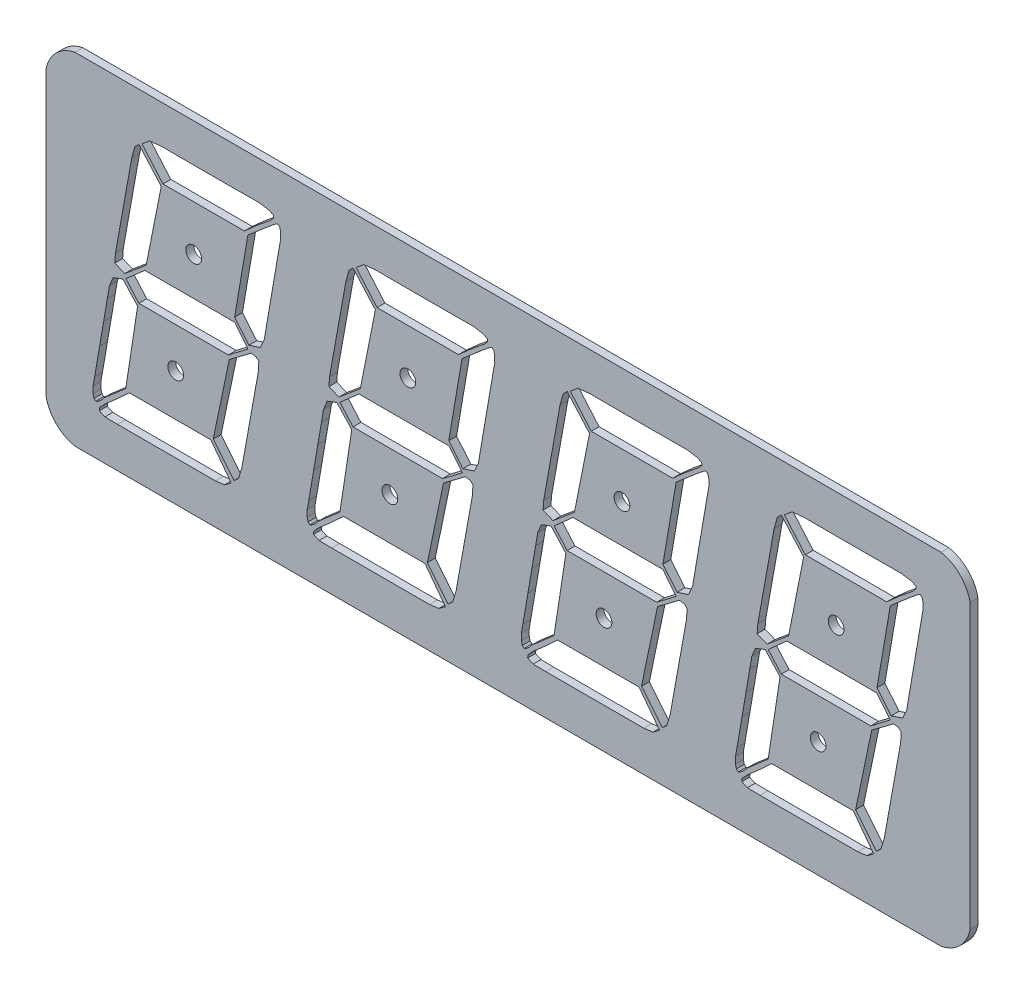
SolidWorks part; units mm, degrees
material "Maple"
ref_plane "Alzado" through (0, 0, 0) normal (0, 0, 1) x (1, 0, 0)
ref_plane "Planta" through (0, 0, 0) normal (0, 1, 0) x (1, 0, 0)
ref_plane "Vista lateral" through (0, 0, 0) normal (1, 0, 0) x (0, 0, -1)
sketch "Model" plane through (0, 0, 0) normal (0, 0, 1) x (1, 0, 0)
  line L311 (169.8255, 67.5031) -> (-160.1745, 67.5031)
  line L328 (148.1981, -37.5509) -> (154.411, -3.0611)
  line L329 (154.411, -3.0611) -> (154.6215, 0.6431)
  line L330 (154.6215, 0.6431) -> (153.5658, 1.5691)
  line L331 (153.5658, 1.5691) -> (151.7361, 1.8778)
  line L332 (151.7361, 1.8778) -> (143.3814, -4.3918)
  line L333 (143.3814, -4.3918) -> (137.2644, -33.698)
  line L334 (137.2644, -33.698) -> (145.1642, -43.466)
  line L335 (145.1642, -43.466) -> (146.9003, -41.9023)
  line L336 (146.9003, -41.9023) -> (148.1981, -37.5509)
  line L337 (106.2034, 43.4858) -> (99.9905, 8.9954)
  line L338 (99.9905, 8.9954) -> (99.7437, 5.6062)
  line L339 (99.7437, 5.6062) -> (103.5436, 4.0578)
  line L340 (103.5436, 4.0578) -> (111.7133, 10.9097)
  line L341 (111.7133, 10.9097) -> (117.4489, 39.7707)
  line L342 (117.4489, 39.7707) -> (108.9383, 49.3712)
  line L343 (108.9383, 49.3712) -> (107.4078, 47.8277)
  line L344 (107.4078, 47.8277) -> (106.2034, 43.4858)
  line L345 (150.4696, 40.2183) -> (145.4043, 10.6009)
  line L346 (145.4043, 10.6009) -> (150.8256, 4.0578)
  line L347 (150.8256, 4.0578) -> (155.1565, 5.4502)
  line L348 (155.1565, 5.4502) -> (156.7122, 8.8717)
  line L349 (156.7122, 8.8717) -> (157.4944, 13.4819)
  line L350 (157.4944, 13.4819) -> (158.8939, 21.6593)
  line L351 (158.8939, 21.6593) -> (160.4266, 30.5868)
  line L352 (160.4266, 30.5868) -> (162.3405, 41.7165)
  line L353 (162.3405, 41.7165) -> (162.9375, 45.066)
  line L354 (162.9375, 45.066) -> (162.9221, 47.52)
  line L355 (162.9221, 47.52) -> (162.5691, 48.9124)
  line L356 (162.5691, 48.9124) -> (161.868, 49.5374)
  line L357 (161.868, 49.5374) -> (161.7578, 49.5282)
  line L358 (161.7578, 49.5282) -> (161.635, 49.4837)
  line L359 (161.635, 49.4837) -> (161.3364, 49.3229)
  line L360 (161.3364, 49.3229) -> (160.5503, 48.7761)
  line L361 (160.5503, 48.7761) -> (158.3402, 46.9717)
  line L362 (158.3402, 46.9717) -> (150.4696, 40.2183)
  line L363 (96.1085, -42.7715) -> (94.0111, -44.9746)
  line L364 (94.0111, -44.9746) -> (93.8733, -46.1445)
  line L365 (93.8733, -46.1445) -> (95.9736, -47.1243)
  line L366 (95.9736, -47.1243) -> (100.8421, -47.1738)
  line L367 (100.8421, -47.1738) -> (138.1093, -47.1738)
  line L368 (138.1093, -47.1738) -> (141.5938, -46.7307)
  line L369 (141.5938, -46.7307) -> (144.1378, -44.8847)
  line L370 (144.1378, -44.8847) -> (136.3412, -34.5114)
  line L371 (136.3412, -34.5114) -> (105.3033, -34.5114)
  line L372 (105.3033, -34.5114) -> (100.112, -39.2778)
  line L373 (100.112, -39.2778) -> (96.1085, -42.7715)
  line L374 (143.0175, -3.1636) -> (150.4696, 2.5031)
  line L375 (150.4696, 2.5031) -> (145.3202, 8.8399)
  line L376 (145.3202, 8.8399) -> (111.039, 8.8399)
  line L377 (111.039, 8.8399) -> (103.9773, 2.5031)
  line L378 (103.9773, 2.5031) -> (108.9226, -3.1636)
  line L379 (108.9226, -3.1636) -> (143.0175, -3.1636)
  line L380 (159.0632, 49.2759) -> (160.2858, 50.6364)
  line L381 (160.2858, 50.6364) -> (160.1964, 51.4631)
  line L382 (160.1964, 51.4631) -> (158.7577, 52.3004)
  line L383 (158.7577, 52.3004) -> (154.753, 52.948)
  line L384 (154.753, 52.948) -> (142.5301, 52.905)
  line L385 (142.5301, 52.905) -> (132.6069, 52.8858)
  line L386 (132.6069, 52.8858) -> (123.3038, 52.8961)
  line L387 (123.3038, 52.8961) -> (117.726, 52.945)
  line L388 (117.726, 52.945) -> (112.9865, 52.4395)
  line L389 (112.9865, 52.4395) -> (110.1277, 50.0329)
  line L390 (110.1277, 50.0329) -> (118.0876, 40.8073)
  line L391 (118.0876, 40.8073) -> (149.1255, 40.8073)
  line L392 (149.1255, 40.8073) -> (153.9859, 45.1352)
  line L393 (153.9859, 45.1352) -> (159.0632, 49.2759)
  line L394 (66.6066, -37.5826) -> (72.8195, -3.0928)
  line L395 (72.8195, -3.0928) -> (73.03, 0.6113)
  line L396 (73.03, 0.6113) -> (71.9743, 1.5374)
  line L397 (71.9743, 1.5374) -> (70.1446, 1.8461)
  line L398 (70.1446, 1.8461) -> (61.7899, -4.4236)
  line L399 (61.7899, -4.4236) -> (55.6728, -33.7298)
  line L400 (55.6728, -33.7298) -> (63.5727, -43.4977)
  line L401 (63.5727, -43.4977) -> (65.3088, -41.9341)
  line L402 (65.3088, -41.9341) -> (66.6066, -37.5826)
  line L403 (24.6119, 43.4541) -> (18.399, 8.9636)
  line L404 (18.399, 8.9636) -> (18.1522, 5.5745)
  line L405 (18.1522, 5.5745) -> (21.9521, 4.026)
  line L406 (21.9521, 4.026) -> (30.1218, 10.8779)
  line L407 (30.1218, 10.8779) -> (35.8574, 39.7389)
  line L408 (35.8574, 39.7389) -> (27.3468, 49.3394)
  line L409 (27.3468, 49.3394) -> (25.8163, 47.7959)
  line L410 (25.8163, 47.7959) -> (24.6119, 43.4541)
  line L411 (68.8781, 40.1866) -> (63.8128, 10.5692)
  line L412 (63.8128, 10.5692) -> (69.2341, 4.026)
  line L413 (69.2341, 4.026) -> (73.565, 5.4185)
  line L414 (73.565, 5.4185) -> (75.1207, 8.8399)
  line L415 (75.1207, 8.8399) -> (75.9029, 13.4502)
  line L416 (75.9029, 13.4502) -> (77.3024, 21.6276)
  line L417 (77.3024, 21.6276) -> (78.8351, 30.5551)
  line L418 (78.8351, 30.5551) -> (80.7489, 41.6847)
  line L419 (80.7489, 41.6847) -> (81.346, 45.0342)
  line L420 (81.346, 45.0342) -> (81.3306, 47.4882)
  line L421 (81.3306, 47.4882) -> (80.9776, 48.8806)
  line L422 (80.9776, 48.8806) -> (80.2764, 49.5056)
  line L423 (80.2764, 49.5056) -> (80.1663, 49.4964)
  line L424 (80.1663, 49.4964) -> (80.0435, 49.452)
  line L425 (80.0435, 49.452) -> (79.7449, 49.2912)
  line L426 (79.7449, 49.2912) -> (78.9588, 48.7444)
  line L427 (78.9588, 48.7444) -> (76.7487, 46.9399)
  line L428 (76.7487, 46.9399) -> (68.8781, 40.1866)
  line L429 (14.517, -42.7715) -> (12.4196, -44.9746)
  line L430 (12.4196, -44.9746) -> (12.2818, -46.1445)
  line L431 (12.2818, -46.1445) -> (14.3821, -47.1243)
  line L432 (14.3821, -47.1243) -> (19.2505, -47.1738)
  line L433 (19.2505, -47.1738) -> (56.5178, -47.1738)
  line L434 (56.5178, -47.1738) -> (60.0023, -46.7307)
  line L435 (60.0023, -46.7307) -> (62.5462, -44.8847)
  line L436 (62.5462, -44.8847) -> (54.7497, -34.5114)
  line L437 (54.7497, -34.5114) -> (23.7118, -34.5114)
  line L438 (23.7118, -34.5114) -> (18.5205, -39.2778)
  line L439 (18.5205, -39.2778) -> (14.517, -42.7715)
  line L440 (61.426, -3.1636) -> (68.8781, 2.5031)
  line L441 (68.8781, 2.5031) -> (63.8128, 8.8399)
  line L442 (63.8128, 8.8399) -> (29.5316, 8.8399)
  line L443 (29.5316, 8.8399) -> (22.3858, 2.5031)
  line L444 (22.3858, 2.5031) -> (27.3311, -3.1636)
  line L445 (27.3311, -3.1636) -> (61.426, -3.1636)
  line L446 (77.4717, 49.2759) -> (78.6943, 50.6364)
  line L447 (78.6943, 50.6364) -> (78.6049, 51.4631)
  line L448 (78.6049, 51.4631) -> (77.1662, 52.3004)
  line L449 (77.1662, 52.3004) -> (73.1615, 52.948)
  line L450 (73.1615, 52.948) -> (60.9385, 52.905)
  line L451 (60.9385, 52.905) -> (51.0154, 52.8858)
  line L452 (51.0154, 52.8858) -> (41.7123, 52.8961)
  line L453 (41.7123, 52.8961) -> (36.1345, 52.945)
  line L454 (36.1345, 52.945) -> (31.395, 52.4395)
  line L455 (31.395, 52.4395) -> (28.5363, 50.0329)
  line L456 (28.5363, 50.0329) -> (36.4961, 40.8073)
  line L457 (36.4961, 40.8073) -> (67.534, 40.8073)
  line L458 (67.534, 40.8073) -> (72.3944, 45.1352)
  line L459 (72.3944, 45.1352) -> (77.4717, 49.2759)
  line L460 (-14.9848, -37.6144) -> (-8.772, -3.1246)
  line L461 (-8.772, -3.1246) -> (-8.5615, 0.5796)
  line L462 (-8.5615, 0.5796) -> (-9.6172, 1.5056)
  line L463 (-9.6172, 1.5056) -> (-11.4469, 1.8143)
  line L464 (-11.4469, 1.8143) -> (-19.8016, -4.4553)
  line L465 (-19.8016, -4.4553) -> (-25.9187, -33.7615)
  line L466 (-25.9187, -33.7615) -> (-18.0188, -43.5295)
  line L467 (-18.0188, -43.5295) -> (-16.2827, -41.9658)
  line L468 (-16.2827, -41.9658) -> (-14.9848, -37.6144)
  line L469 (-56.9796, 43.4223) -> (-63.1925, 8.9319)
  line L470 (-63.1925, 8.9319) -> (-63.4393, 5.5427)
  line L471 (-63.4393, 5.5427) -> (-59.6394, 3.9943)
  line L472 (-59.6394, 3.9943) -> (-51.4697, 10.8462)
  line L473 (-51.4697, 10.8462) -> (-45.7341, 39.7072)
  line L474 (-45.7341, 39.7072) -> (-54.2447, 49.3077)
  line L475 (-54.2447, 49.3077) -> (-55.7752, 47.7642)
  line L476 (-55.7752, 47.7642) -> (-56.9796, 43.4223)
  line L477 (-12.7134, 40.1548) -> (-17.7787, 10.5374)
  line L478 (-17.7787, 10.5374) -> (-12.3574, 3.9943)
  line L479 (-12.3574, 3.9943) -> (-8.0265, 5.3867)
  line L480 (-8.0265, 5.3867) -> (-6.4708, 8.8082)
  line L481 (-6.4708, 8.8082) -> (-5.6886, 13.4184)
  line L482 (-5.6886, 13.4184) -> (-4.2891, 21.5958)
  line L483 (-4.2891, 21.5958) -> (-2.7564, 30.5233)
  line L484 (-2.7564, 30.5233) -> (-0.8426, 41.653)
  line L485 (-0.8426, 41.653) -> (-0.2455, 45.0025)
  line L486 (-0.2455, 45.0025) -> (-0.2609, 47.4565)
  line L487 (-0.2609, 47.4565) -> (-0.6139, 48.8489)
  line L488 (-0.6139, 48.8489) -> (-1.3151, 49.4739)
  line L489 (-1.3151, 49.4739) -> (-1.4252, 49.4647)
  line L490 (-1.4252, 49.4647) -> (-1.548, 49.4202)
  line L491 (-1.548, 49.4202) -> (-1.8466, 49.2594)
  line L492 (-1.8466, 49.2594) -> (-2.6327, 48.7126)
  line L493 (-2.6327, 48.7126) -> (-4.8428, 46.9082)
  line L494 (-4.8428, 46.9082) -> (-12.7134, 40.1548)
  line L495 (-67.0745, -42.7715) -> (-69.1719, -44.9746)
  line L496 (-69.1719, -44.9746) -> (-69.3097, -46.1445)
  line L497 (-69.3097, -46.1445) -> (-67.2094, -47.1243)
  line L498 (-67.2094, -47.1243) -> (-62.3409, -47.1738)
  line L499 (-62.3409, -47.1738) -> (-25.0737, -47.1738)
  line L500 (-21.5892, -46.7307) -> (-19.0452, -44.8847)
  line L501 (-19.0452, -44.8847) -> (-26.8418, -34.5114)
  line L502 (-26.8418, -34.5114) -> (-57.8797, -34.5114)
  line L503 (-57.8797, -34.5114) -> (-63.071, -39.2778)
  line L504 (-63.071, -39.2778) -> (-67.0745, -42.7715)
  line L505 (-20.1655, -3.1636) -> (-12.5898, 2.5031)
  line L506 (-12.5898, 2.5031) -> (-17.7064, 8.8399)
  line L507 (-17.7064, 8.8399) -> (-51.9875, 8.8399)
  line L508 (-51.9875, 8.8399) -> (-59.2057, 2.5031)
  line L509 (-59.2057, 2.5031) -> (-54.2604, -3.1636)
  line L510 (-54.2604, -3.1636) -> (-20.1655, -3.1636)
  line L511 (-4.1198, 49.2759) -> (-2.8972, 50.6364)
  line L512 (-2.8972, 50.6364) -> (-2.9866, 51.4631)
  line L513 (-2.9866, 51.4631) -> (-4.4253, 52.3004)
  line L514 (-4.4253, 52.3004) -> (-8.4299, 52.948)
  line L515 (-8.4299, 52.948) -> (-20.653, 52.905)
  line L516 (-20.653, 52.905) -> (-30.5761, 52.8858)
  line L517 (-30.5761, 52.8858) -> (-39.8792, 52.8961)
  line L518 (-39.8792, 52.8961) -> (-45.4569, 52.945)
  line L519 (-45.4569, 52.945) -> (-50.1965, 52.4395)
  line L520 (-50.1965, 52.4395) -> (-53.0552, 50.0329)
  line L521 (-53.0552, 50.0329) -> (-45.0954, 40.8073)
  line L522 (-45.0954, 40.8073) -> (-14.0575, 40.8073)
  line L523 (-14.0575, 40.8073) -> (-9.1971, 45.1352)
  line L524 (-9.1971, 45.1352) -> (-4.1198, 49.2759)
  line L525 (-96.5763, -37.6461) -> (-90.3635, -3.1563)
  line L526 (-90.3635, -3.1563) -> (-90.153, 0.5478)
  line L527 (-90.153, 0.5478) -> (-91.2088, 1.4739)
  line L528 (-91.2088, 1.4739) -> (-93.0384, 1.7826)
  line L529 (-93.0384, 1.7826) -> (-101.3931, -4.4871)
  line L530 (-101.3931, -4.4871) -> (-107.5102, -33.7933)
  line L531 (-107.5102, -33.7933) -> (-99.6103, -43.5612)
  line L532 (-99.6103, -43.5612) -> (-97.8742, -41.9976)
  line L533 (-97.8742, -41.9976) -> (-96.5763, -37.6461)
  line L534 (-138.5711, 43.3906) -> (-144.784, 8.9001)
  line L535 (-144.784, 8.9001) -> (-145.0308, 5.511)
  line L536 (-145.0308, 5.511) -> (-141.2308, 3.9625)
  line L537 (-141.2308, 3.9625) -> (-133.0612, 10.8144)
  line L538 (-133.0612, 10.8144) -> (-127.3256, 39.6754)
  line L539 (-127.3256, 39.6754) -> (-135.8362, 49.2759)
  line L540 (-135.8362, 49.2759) -> (-137.3667, 47.7324)
  line L541 (-137.3667, 47.7324) -> (-138.5711, 43.3906)
  line L542 (-94.3049, 40.1231) -> (-99.3702, 10.5057)
  line L543 (-99.3702, 10.5057) -> (-93.9488, 3.9625)
  line L544 (-93.9488, 3.9625) -> (-89.618, 5.355)
  line L545 (-89.618, 5.355) -> (-88.0623, 8.7764)
  line L546 (-88.0623, 8.7764) -> (-87.2801, 13.3867)
  line L547 (-87.2801, 13.3867) -> (-85.8806, 21.5641)
  line L548 (-85.8806, 21.5641) -> (-84.3479, 30.4916)
  line L549 (-84.3479, 30.4916) -> (-82.434, 41.6212)
  line L550 (-82.434, 41.6212) -> (-81.8371, 44.9707)
  line L551 (-81.8371, 44.9707) -> (-81.8524, 47.4247)
  line L552 (-81.8524, 47.4247) -> (-82.2054, 48.8171)
  line L553 (-82.2054, 48.8171) -> (-82.9066, 49.4421)
  line L554 (-82.9066, 49.4421) -> (-83.0167, 49.4329)
  line L555 (-83.0167, 49.4329) -> (-83.1395, 49.3885)
  line L556 (-83.1395, 49.3885) -> (-83.4381, 49.2277)
  line L557 (-83.4381, 49.2277) -> (-84.2242, 48.6809)
  line L558 (-84.2242, 48.6809) -> (-86.4343, 46.8764)
  line L559 (-86.4343, 46.8764) -> (-94.3049, 40.1231)
  line L560 (-148.666, -42.7715) -> (-150.7634, -44.9746)
  line L561 (-150.7634, -44.9746) -> (-150.9012, -46.1445)
  line L562 (-150.9012, -46.1445) -> (-148.8009, -47.1243)
  line L563 (-148.8009, -47.1243) -> (-143.9324, -47.1738)
  line L564 (-143.9324, -47.1738) -> (-106.6652, -47.1738)
  line L565 (-106.6652, -47.1738) -> (-103.1807, -46.7307)
  line L566 (-103.1807, -46.7307) -> (-100.6367, -44.8847)
  line L567 (-100.6367, -44.8847) -> (-108.4333, -34.5114)
  line L568 (-108.4333, -34.5114) -> (-139.4712, -34.5114)
  line L569 (-139.4712, -34.5114) -> (-144.6625, -39.2778)
  line L570 (-144.6625, -39.2778) -> (-148.666, -42.7715)
  line L571 (-101.757, -3.1636) -> (-94.3049, 2.5031)
  line L572 (-94.3049, 2.5031) -> (-99.2979, 8.8399)
  line L573 (-99.2979, 8.8399) -> (-133.579, 8.8399)
  line L574 (-133.579, 8.8399) -> (-140.7972, 2.5031)
  line L575 (-140.7972, 2.5031) -> (-135.8519, -3.1636)
  line L576 (-135.8519, -3.1636) -> (-101.757, -3.1636)
  line L577 (-85.7112, 49.2759) -> (-84.4888, 50.6364)
  line L578 (-84.4888, 50.6364) -> (-84.5781, 51.4631)
  line L579 (-84.5781, 51.4631) -> (-86.0168, 52.3004)
  line L580 (-86.0168, 52.3004) -> (-90.0214, 52.948)
  line L581 (-90.0214, 52.948) -> (-102.2445, 52.905)
  line L582 (-102.2445, 52.905) -> (-112.1676, 52.8858)
  line L583 (-112.1676, 52.8858) -> (-121.4707, 52.8961)
  line L584 (-121.4707, 52.8961) -> (-127.0484, 52.945)
  line L585 (-127.0484, 52.945) -> (-131.788, 52.4395)
  line L586 (-131.788, 52.4395) -> (-134.6467, 50.0329)
  line L587 (-134.6467, 50.0329) -> (-126.6869, 40.8073)
  line L588 (-126.6869, 40.8073) -> (-95.649, 40.8073)
  line L589 (-95.649, 40.8073) -> (-90.7886, 45.1352)
  line L590 (-90.7886, 45.1352) -> (-85.7112, 49.2759)
  line L591 (103.9312, -33.7005) -> (108.4464, -4.2669)
  line L592 (108.4464, -4.2669) -> (102.8036, 1.8899)
  line L593 (102.8036, 1.8899) -> (99.0967, 0.4877)
  line L594 (99.0967, 0.4877) -> (97.6904, -2.9361)
  line L595 (97.6904, -2.9361) -> (96.9084, -7.5465)
  line L596 (96.9084, -7.5465) -> (95.5093, -15.7241)
  line L597 (95.5093, -15.7241) -> (93.9771, -24.652)
  line L598 (93.9771, -24.652) -> (92.064, -35.7821)
  line L599 (92.064, -35.7821) -> (91.4651, -39.1304)
  line L600 (91.4651, -39.1304) -> (91.4799, -41.5844)
  line L601 (91.4799, -41.5844) -> (91.8339, -42.9773)
  line L602 (91.8339, -42.9773) -> (92.5347, -43.6018)
  line L603 (95.4844, -41.0349) -> (103.9312, -33.7005)
  line L604 (22.3397, -33.7322) -> (26.8549, -4.2986)
  line L605 (26.8549, -4.2986) -> (21.2122, 1.8582)
  line L606 (21.2122, 1.8582) -> (17.5052, 0.4559)
  line L607 (17.5052, 0.4559) -> (16.0989, -2.9679)
  line L608 (16.0989, -2.9679) -> (15.3169, -7.5782)
  line L609 (15.3169, -7.5782) -> (13.9178, -15.7559)
  line L610 (13.9178, -15.7559) -> (12.3856, -24.6838)
  line L611 (12.3856, -24.6838) -> (10.4725, -35.8139)
  line L612 (10.4725, -35.8139) -> (9.8736, -39.1621)
  line L613 (9.8736, -39.1621) -> (9.8884, -41.6162)
  line L614 (9.8884, -41.6162) -> (10.2424, -43.0091)
  line L615 (10.2424, -43.0091) -> (10.9432, -43.6336)
  line L616 (13.8929, -41.0666) -> (22.3397, -33.7322)
  line L617 (-59.2518, -33.764) -> (-54.7366, -4.3304)
  line L618 (-54.7366, -4.3304) -> (-60.3793, 1.8264)
  line L619 (-60.3793, 1.8264) -> (-64.0863, 0.4242)
  line L620 (-64.0863, 0.4242) -> (-65.4926, -2.9996)
  line L621 (-65.4926, -2.9996) -> (-66.2746, -7.61)
  line L622 (-66.2746, -7.61) -> (-67.6737, -15.7876)
  line L623 (-67.6737, -15.7876) -> (-69.2059, -24.7155)
  line L624 (-69.2059, -24.7155) -> (-71.119, -35.8456)
  line L625 (-71.119, -35.8456) -> (-71.7179, -39.1939)
  line L626 (-71.7179, -39.1939) -> (-71.7031, -41.6479)
  line L627 (-71.7031, -41.6479) -> (-71.3491, -43.0408)
  line L628 (-71.3491, -43.0408) -> (-70.6483, -43.6653)
  line L629 (-67.6986, -41.0984) -> (-59.2518, -33.764)
  line L630 (-140.8433, -33.7957) -> (-136.3281, -4.3621)
  line L631 (-136.3281, -4.3621) -> (-141.9708, 1.7947)
  line L632 (-141.9708, 1.7947) -> (-145.6778, 0.3924)
  line L633 (-145.6778, 0.3924) -> (-147.0841, -3.0314)
  line L634 (-147.0841, -3.0314) -> (-147.8661, -7.6417)
  line L635 (-147.8661, -7.6417) -> (-149.2652, -15.8194)
  line L636 (-149.2652, -15.8194) -> (-150.7974, -24.7473)
  line L637 (-150.7974, -24.7473) -> (-152.7104, -35.8774)
  line L638 (-152.7104, -35.8774) -> (-153.3094, -39.2256)
  line L639 (-153.3094, -39.2256) -> (-153.2946, -41.6797)
  line L640 (-153.2946, -41.6797) -> (-152.9406, -43.0726)
  line L641 (-152.9406, -43.0726) -> (-152.2398, -43.6971)
  line L642 (-149.2901, -41.1301) -> (-140.8433, -33.7957)
  line L643 (180.8859, -51.4365) -> (180.8859, 56.4428)
  line L644 (-160.1745, -62.4969) -> (169.8255, -62.4969)
  line L645 (-171.2349, 56.4428) -> (-171.2349, -51.4365)
  line L646 (-25.0737, -47.1738) -> (-21.5892, -46.7307)
  circle A0 centre (-114.9449, 23.4531) radius 3
  circle A1 centre (-121.8049, -18.4569) radius 3
  circle A2 centre (-33.3549, 23.4531) radius 3
  circle A3 centre (-40.2149, -18.4569) radius 3
  circle A4 centre (48.2351, 23.4531) radius 3
  circle A5 centre (41.3751, -18.4569) radius 3
  circle A7 centre (129.8251, 23.4531) radius 3
  circle A8 centre (122.9651, -18.4569) radius 3
  arc A30 (92.5347, -43.6018) -> (95.4844, -41.0349) centre (89.8145, -37.4978) ccw
  arc A31 (10.9432, -43.6336) -> (13.8929, -41.0666) centre (8.2231, -37.5297) ccw
  arc A32 (-70.6483, -43.6653) -> (-67.6986, -41.0984) centre (-73.3686, -37.5613) ccw
  arc A33 (-152.2398, -43.6971) -> (-149.2901, -41.1301) centre (-154.9605, -37.5925) ccw
  arc A34 (180.8859, 56.4428) -> (169.8255, 67.5031) centre (167.1449, 53.7622) ccw
  arc A35 (-171.2349, -51.4365) -> (-160.1745, -62.4969) centre (-157.4939, -48.7559) ccw
  arc A36 (-160.1745, 67.5031) -> (-171.2349, 56.4428) centre (-157.4939, 53.7622) ccw
  arc A37 (169.8255, -62.4969) -> (180.8859, -51.4365) centre (167.1449, -48.7559) ccw
  dimension "D3" = 44.05
  dimension "D4" = 6
  dimension "D5" = 56.29
  dimension "D6" = 44.04
  dimension "D7" = 6
  dimension "D8" = 49.43
  dimension "D1" = 130
  dimension "D2" = 352.1207
  dimension "D9" = 4
extrude "Saliente-Extruir1" add sketch "Model" along normal blind 3
